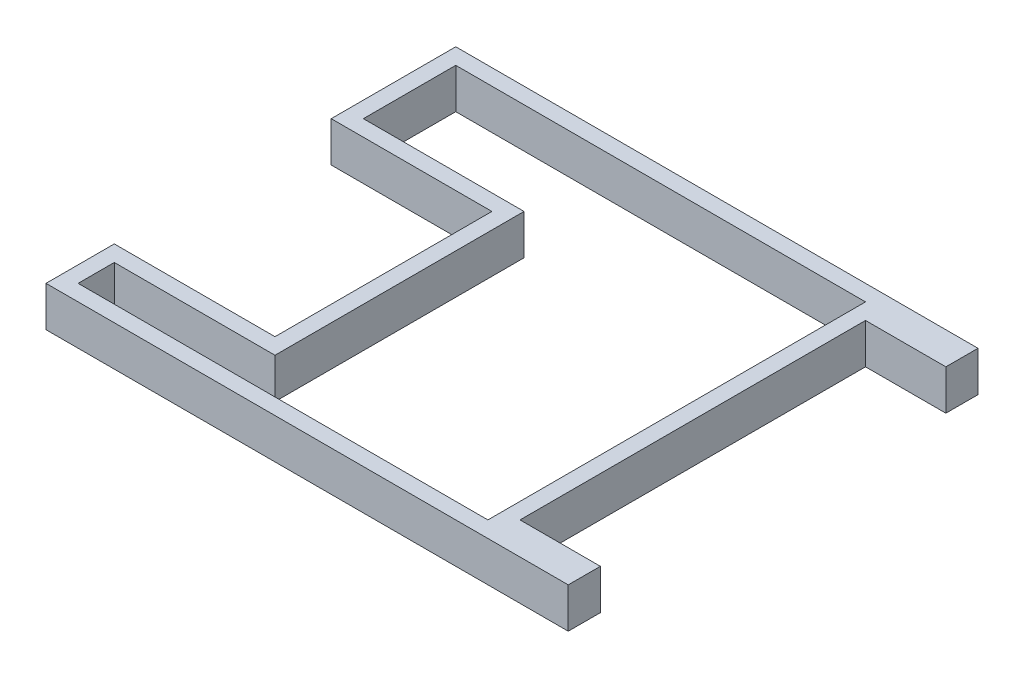
SolidWorks part; units mm, degrees
ref_plane "前视基准面" through (0, 0, 0) normal (0, 0, 1) x (1, 0, 0)
ref_plane "上视基准面" through (0, 0, 0) normal (0, 1, 0) x (1, 0, 0)
ref_plane "右视基准面" through (0, 0, 0) normal (1, 0, 0) x (0, 0, -1)
sketch "草图1" plane through (0, 0, 0) normal (0, 1, 0) x (1, 0, 0)
  line L0 (-44.7751, 5.6464) -> (-24.7751, 5.6464)
  line L1 (-44.7751, 21.1464) -> (20.2249, 21.1464) construction
  line L5 (-24.7751, 5.6464) -> (-24.7751, -21.3536)
  line L6 (-24.7751, -21.3536) -> (-44.7751, -21.3536)
  line L7 (-44.7751, -21.3536) -> (-44.7751, -29.8536)
  line L8 (-44.7751, -29.8536) -> (20.2249, -29.8536)
  line L9 (-44.7751, 21.1464) -> (20.2249, 21.1464)
  line L10 (20.2249, 21.1464) -> (20.2249, 17.1464)
  line L11 (20.2249, 17.1464) -> (10.2249, 17.1464)
  line L12 (10.2249, 17.1464) -> (10.2249, -25.8536)
  line L13 (10.2249, -25.8536) -> (20.2249, -25.8536)
  line L14 (20.2249, -25.8536) -> (20.2249, -29.8536)
  line L15 (-44.7751, 21.1464) -> (-44.7751, 5.6464)
  line L30 (-42.7751, 19.1464) -> (8.2249, 19.1464)
  line L31 (8.2249, 19.1464) -> (8.2249, -27.8536)
  line L32 (8.2249, -27.8536) -> (-42.7751, -27.8536)
  line L33 (-42.7751, -27.8536) -> (-42.7751, -23.3536)
  line L34 (-42.7751, -23.3536) -> (-22.7751, -23.3536)
  line L35 (-22.7751, -23.3536) -> (-22.7751, 7.6464)
  line L36 (-22.7751, 7.6464) -> (-42.7751, 7.6464)
  line L37 (-42.7751, 7.6464) -> (-42.7751, 19.1464)
  point P20 (-42.7751, -25.6036)
  dimension "D1" = 43
  dimension "D2" = 27
  dimension "D3" = 4
  dimension "D4" = 20
  dimension "D5" = 10
  dimension "D6" = 4
  dimension "D7" = 35
  dimension "D8" = 8.5
  dimension "D9" = 2
  dimension "D10" = 2
  dimension "D11" = 2
  dimension "D12" = 2
  dimension "D13" = 2
  dimension "D14" = 2
  dimension "D15" = 2
  dimension "D16" = 2
extrude "凸台-拉伸4" add sketch "草图1" along normal blind 5
